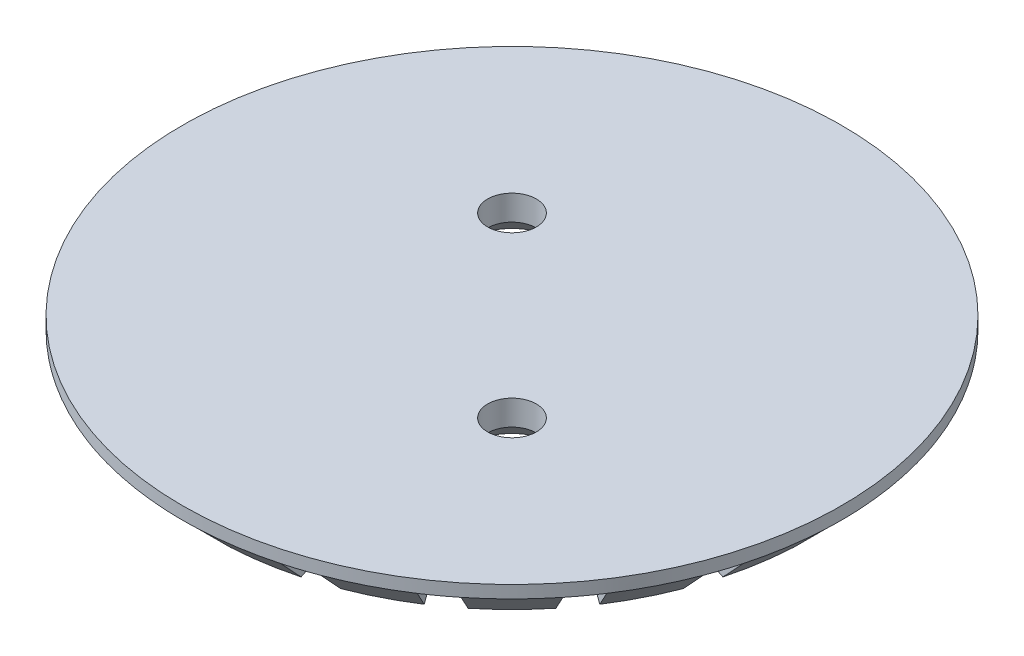
SolidWorks part; units mm, degrees
ref_plane "Front Plane" through (0, 0, 0) normal (0, 0, 1) x (1, 0, 0)
ref_plane "Top Plane" through (0, 0, 0) normal (0, 1, 0) x (1, 0, 0)
ref_plane "Right Plane" through (0, 0, 0) normal (1, 0, 0) x (0, 0, -1)
sketch "Sketch1" plane through (0, 0, 0) normal (0, 1, 0) x (-1, 0, 0)
  arc A4 (-31.9412, 19.937) -> (-31.9412, -14.163) centre (-31.9412, 2.887) ccw
  arc A5 (-31.9412, -14.163) -> (-31.9412, 19.937) centre (-31.9412, 2.887) ccw
  arc A12 (-37.598, -1.7449) -> (-37.598, -3.7949) centre (-37.598, -2.7699) ccw
  arc A13 (-37.598, -3.7949) -> (-37.598, -1.7449) centre (-37.598, -2.7699) ccw
  arc A14 (-26.2843, -1.7449) -> (-26.2843, -3.7949) centre (-26.2843, -2.7699) ccw
  arc A15 (-26.2843, -3.7949) -> (-26.2843, -1.7449) centre (-26.2843, -2.7699) ccw
  arc A16 (-26.2843, 9.5689) -> (-26.2843, 7.5189) centre (-26.2843, 8.5439) ccw
  arc A17 (-26.2843, 7.5189) -> (-26.2843, 9.5689) centre (-26.2843, 8.5439) ccw
  arc A18 (-37.598, 9.5689) -> (-37.598, 7.5189) centre (-37.598, 8.5439) ccw
  arc A19 (-37.598, 7.5189) -> (-37.598, 9.5689) centre (-37.598, 8.5439) ccw
sketch "Sketch2" plane through (0, 0, 0) normal (0, 1, 0) x (1, 0, 0)
  line L0 (31.9412, -2.887) -> (46.7904, 11.9622) construction
  line L1 (46.7904, 11.9622) -> (17.0919, -17.7362) construction
  line L2 (31.9412, -2.887) -> (52.9412, -2.887) construction
  circle A0 centre (31.9412, -2.887) radius 21
  circle A2 centre (41.1336, 6.3054) radius 7.5
  circle A3 centre (22.7488, -12.0794) radius 7.5
  point P3 (26.2843, 2.7699)
  point P4 (37.598, 2.7699)
  point P5 (37.598, -8.5439)
  point P8 (26.2843, -8.5439)
  dimension "D1" = 42
  dimension "D2" = 15
  dimension "D3" = 135
  dimension "D4" = 8
  dimension "D5" = 8
extrude "Boss-Extrude1" add sketch "Sketch2" along normal blind 2.8 contours A0 A3 A2 | A3 | A2
sketch "Sketch3" plane through (0, 0, 0) normal (0, 1, 0) x (1, 0, 0)
  point P0 (26.2843, 2.7699)
  point P1 (37.598, 2.7699)
  point P3 (37.598, -8.5439)
  point P5 (26.2843, -8.5439)
hole_wizard "CSK for M2.5 Flat Head Machine Screw1" positions "Sketch3" profile "Sketch4" countersink size "M2.5" standard "ANSI Metric"
sketch "Sketch4" plane through (26.2843, 0, -2.7699) normal (1, 0, 0) x (0, 0, -1)
  line L0 (0, 0) -> (0, 2.8)
  line L1 (0, 2.8) -> (1.55, 2.8)
  line L2 (1.55, 2.8) -> (1.55, 1.2)
  line L3 (1.55, 1.2) -> (2.75, 0)
  line L5 (2.75, 0) -> (0, 0)
  line L6 (-1.55, 1.2) -> (-2.75, 0) construction
  line L11 (0, -6.35) -> (0, 107.95) construction
  dimension "Thru Hole Dia." = 3.1
  dimension "Thru Hole Depth" = 2.8
  dimension "Near C'Sink Dia." = 5.5
  dimension "Near C'Sink Angle" = 90
chamfer "Chamfer1" distance 2 angle 45 1 edges at (31.9412, 0, 23.887)
sketch "Sketch5" plane through (0, 0, 0) normal (0, -1, 0) x (1, 0, 0)
  line L0 (31.9412, 23.887) -> (31.9412, 15.8632) construction
  line L1 (30.9412, 23.8632) -> (30.9412, 15.8632)
  line L2 (30.9412, 15.8632) -> (32.9412, 15.8632)
  line L3 (32.9412, 15.8632) -> (32.9412, 23.8632)
  line L4 (30.9412, 23.8632) -> (30.9412, 24.9995)
  line L5 (30.9412, 24.9995) -> (32.9412, 24.9995)
  line L6 (32.9412, 24.9995) -> (32.9412, 23.8632)
  line L7 (39.7254, 23.6082) -> (39.3742, 22.5275)
  line L8 (36.9021, 14.9191) -> (39.3742, 22.5275)
  line L9 (35, 15.5371) -> (36.9021, 14.9191)
  line L10 (37.4721, 23.1455) -> (35, 15.5371)
  line L11 (37.4721, 23.1455) -> (37.8232, 24.2262)
  line L12 (37.8232, 24.2262) -> (39.7254, 23.6082)
  line L13 (45.7476, 20.1886) -> (45.0797, 19.2693)
  line L14 (40.3774, 12.7972) -> (45.0797, 19.2693)
  line L15 (38.7594, 13.9727) -> (40.3774, 12.7972)
  line L16 (43.4616, 20.4449) -> (38.7594, 13.9727)
  line L17 (43.4616, 20.4449) -> (44.1295, 21.3642)
  line L18 (44.1295, 21.3642) -> (45.7476, 20.1886)
  line L19 (50.4183, 15.0754) -> (49.499, 14.4075)
  line L20 (43.0269, 9.7052) -> (49.499, 14.4075)
  line L21 (41.8513, 11.3232) -> (43.0269, 9.7052)
  line L22 (48.3235, 16.0255) -> (41.8513, 11.3232)
  line L23 (48.3235, 16.0255) -> (49.2428, 16.6934)
  line L24 (49.2428, 16.6934) -> (50.4183, 15.0754)
  line L25 (53.2804, 8.7691) -> (52.1997, 8.4179)
  line L26 (44.5913, 5.9458) -> (52.1997, 8.4179)
  line L27 (43.9732, 7.8479) -> (44.5913, 5.9458)
  line L28 (51.5817, 10.32) -> (43.9732, 7.8479)
  line L29 (51.5817, 10.32) -> (52.6624, 10.6712)
  line L30 (52.6624, 10.6712) -> (53.2804, 8.7691)
  line L31 (54.0537, 1.887) -> (52.9173, 1.887)
  line L32 (44.9173, 1.887) -> (52.9173, 1.887)
  line L33 (44.9173, 3.887) -> (44.9173, 1.887)
  line L34 (52.9173, 3.887) -> (44.9173, 3.887)
  line L35 (52.9173, 3.887) -> (54.0537, 3.887)
  line L36 (54.0537, 3.887) -> (54.0537, 1.887)
  line L37 (52.6624, -4.8972) -> (51.5817, -4.5461)
  line L38 (43.9732, -2.0739) -> (51.5817, -4.5461)
  line L39 (44.5913, -0.1718) -> (43.9732, -2.0739)
  line L40 (52.1997, -2.6439) -> (44.5913, -0.1718)
  line L41 (52.1997, -2.6439) -> (53.2804, -2.9951)
  line L42 (53.2804, -2.9951) -> (52.6624, -4.8972)
  line L43 (49.2428, -10.9194) -> (48.3235, -10.2515)
  line L44 (41.8513, -5.5492) -> (48.3235, -10.2515)
  line L45 (43.0269, -3.9312) -> (41.8513, -5.5492)
  line L46 (49.499, -8.6335) -> (43.0269, -3.9312)
  line L47 (49.499, -8.6335) -> (50.4183, -9.3014)
  line L48 (50.4183, -9.3014) -> (49.2428, -10.9194)
  line L49 (44.1295, -15.5902) -> (43.4616, -14.6709)
  line L50 (38.7594, -8.1987) -> (43.4616, -14.6709)
  line L51 (40.3774, -7.0232) -> (38.7594, -8.1987)
  line L52 (45.0797, -13.4953) -> (40.3774, -7.0232)
  line L53 (45.0797, -13.4953) -> (45.7476, -14.4146)
  line L54 (45.7476, -14.4146) -> (44.1295, -15.5902)
  line L55 (37.8232, -18.4522) -> (37.4721, -17.3716)
  line L56 (35, -9.7631) -> (37.4721, -17.3716)
  line L57 (36.9021, -9.1451) -> (35, -9.7631)
  line L58 (39.3742, -16.7535) -> (36.9021, -9.1451)
  line L59 (39.3742, -16.7535) -> (39.7254, -17.8342)
  line L60 (39.7254, -17.8342) -> (37.8232, -18.4522)
  line L61 (30.9412, -19.2255) -> (30.9412, -18.0892)
  line L62 (30.9412, -10.0892) -> (30.9412, -18.0892)
  line L63 (32.9412, -10.0892) -> (30.9412, -10.0892)
  line L64 (32.9412, -18.0892) -> (32.9412, -10.0892)
  line L65 (32.9412, -18.0892) -> (32.9412, -19.2255)
  line L66 (32.9412, -19.2255) -> (30.9412, -19.2255)
  line L67 (24.157, -17.8342) -> (24.5081, -16.7535)
  line L68 (26.9803, -9.1451) -> (24.5081, -16.7535)
  line L69 (28.8824, -9.7631) -> (26.9803, -9.1451)
  line L70 (26.4102, -17.3716) -> (28.8824, -9.7631)
  line L71 (26.4102, -17.3716) -> (26.0591, -18.4522)
  line L72 (26.0591, -18.4522) -> (24.157, -17.8342)
  line L73 (18.1348, -14.4146) -> (18.8027, -13.4953)
  line L74 (23.5049, -7.0232) -> (18.8027, -13.4953)
  line L75 (25.123, -8.1987) -> (23.5049, -7.0232)
  line L76 (20.4207, -14.6709) -> (25.123, -8.1987)
  line L77 (20.4207, -14.6709) -> (19.7528, -15.5902)
  line L78 (19.7528, -15.5902) -> (18.1348, -14.4146)
  line L79 (13.464, -9.3014) -> (14.3833, -8.6335)
  line L80 (20.8554, -3.9312) -> (14.3833, -8.6335)
  line L81 (22.031, -5.5492) -> (20.8554, -3.9312)
  line L82 (15.5589, -10.2515) -> (22.031, -5.5492)
  line L83 (15.5589, -10.2515) -> (14.6396, -10.9194)
  line L84 (14.6396, -10.9194) -> (13.464, -9.3014)
  line L85 (10.6019, -2.9951) -> (11.6826, -2.6439)
  line L86 (19.2911, -0.1718) -> (11.6826, -2.6439)
  line L87 (19.9091, -2.0739) -> (19.2911, -0.1718)
  line L88 (12.3007, -4.5461) -> (19.9091, -2.0739)
  line L89 (12.3007, -4.5461) -> (11.22, -4.8972)
  line L90 (11.22, -4.8972) -> (10.6019, -2.9951)
  line L91 (9.8287, 3.887) -> (10.965, 3.887)
  line L92 (18.965, 3.887) -> (10.965, 3.887)
  line L93 (18.965, 1.887) -> (18.965, 3.887)
  line L94 (10.965, 1.887) -> (18.965, 1.887)
  line L95 (10.965, 1.887) -> (9.8287, 1.887)
  line L96 (9.8287, 1.887) -> (9.8287, 3.887)
  line L97 (11.22, 10.6712) -> (12.3007, 10.32)
  line L98 (19.9091, 7.8479) -> (12.3007, 10.32)
  line L99 (19.2911, 5.9458) -> (19.9091, 7.8479)
  line L100 (11.6826, 8.4179) -> (19.2911, 5.9458)
  line L101 (11.6826, 8.4179) -> (10.6019, 8.7691)
  line L102 (10.6019, 8.7691) -> (11.22, 10.6712)
  line L103 (14.6396, 16.6934) -> (15.5589, 16.0255)
  line L104 (22.031, 11.3232) -> (15.5589, 16.0255)
  line L105 (20.8554, 9.7052) -> (22.031, 11.3232)
  line L106 (14.3833, 14.4075) -> (20.8554, 9.7052)
  line L107 (14.3833, 14.4075) -> (13.464, 15.0754)
  line L108 (13.464, 15.0754) -> (14.6396, 16.6934)
  line L109 (19.7528, 21.3642) -> (20.4207, 20.4449)
  line L110 (25.123, 13.9727) -> (20.4207, 20.4449)
  line L111 (23.5049, 12.7972) -> (25.123, 13.9727)
  line L112 (18.8027, 19.2693) -> (23.5049, 12.7972)
  line L113 (18.8027, 19.2693) -> (18.1348, 20.1886)
  line L114 (18.1348, 20.1886) -> (19.7528, 21.3642)
  line L115 (26.0591, 24.2262) -> (26.4102, 23.1455)
  line L116 (28.8824, 15.5371) -> (26.4102, 23.1455)
  line L117 (26.9803, 14.9191) -> (28.8824, 15.5371)
  line L118 (24.5081, 22.5275) -> (26.9803, 14.9191)
  line L119 (24.5081, 22.5275) -> (24.157, 23.6082)
  line L120 (24.157, 23.6082) -> (26.0591, 24.2262)
  circle A0 centre (31.9412, 2.887) radius 21 construction
  circle A1 centre (31.9412, 2.887) radius 21
  point P7 (31.9412, 2.887)
  circle M14 centre (31.9412, 2.887) radius 19
  dimension "D1" = 8
  dimension "D2" = 2
  dimension "D3" = 20
extrude "Cut-Extrude1" cut sketch "Sketch5" against normal blind 2 contours L88 L87 L86 M14 | L82 L81 L80 M14 | L76 L75 L74 M14 | L74 A1 L76 M14 | L68 A1 L70 M14 | L70 L69 L68 M14 | L64 L63 L62 M14 | L62 A1 L64 M14 | L58 L57 L56 M14 | L56 A1 L58 M14 | L52 L51 L50 M14 | L50 A1 L52 M14 | L46 L45 L44 M14 | L44 A1 L46 M14 | L40 L39 L38 M14 | L38 A1 L40 M14 | L32 A1 L34 M14 | L34 L33 L32 M14 | L26 A1 L28 M14 | L28 L27 L26 M14 | L20 A1 L22 M14 | L22 L21 L20 M14 | L14 A1 L16 M14 | L16 L15 L14 M14 | L8 A1 L10 M14 | L10 L9 L8 M14 | A1 L0 L3 M14 | L0 A1 L1 M14 | L0 L2 L3 M14 | L0 L1 L2 M14 | L118 L117 L116 M14 | L116 A1 L118 M14 | L110 A1 L112 M14 | L112 L111 L110 M14 | L104 A1 L106 M14 | L106 L105 L104 M14 | L98 A1 L100 M14 | L100 L99 L98 M14 | L92 A1 L94 M14 | L94 L93 L92 M14 | L86 A1 L88 M14 | L80 A1 L82 M14
